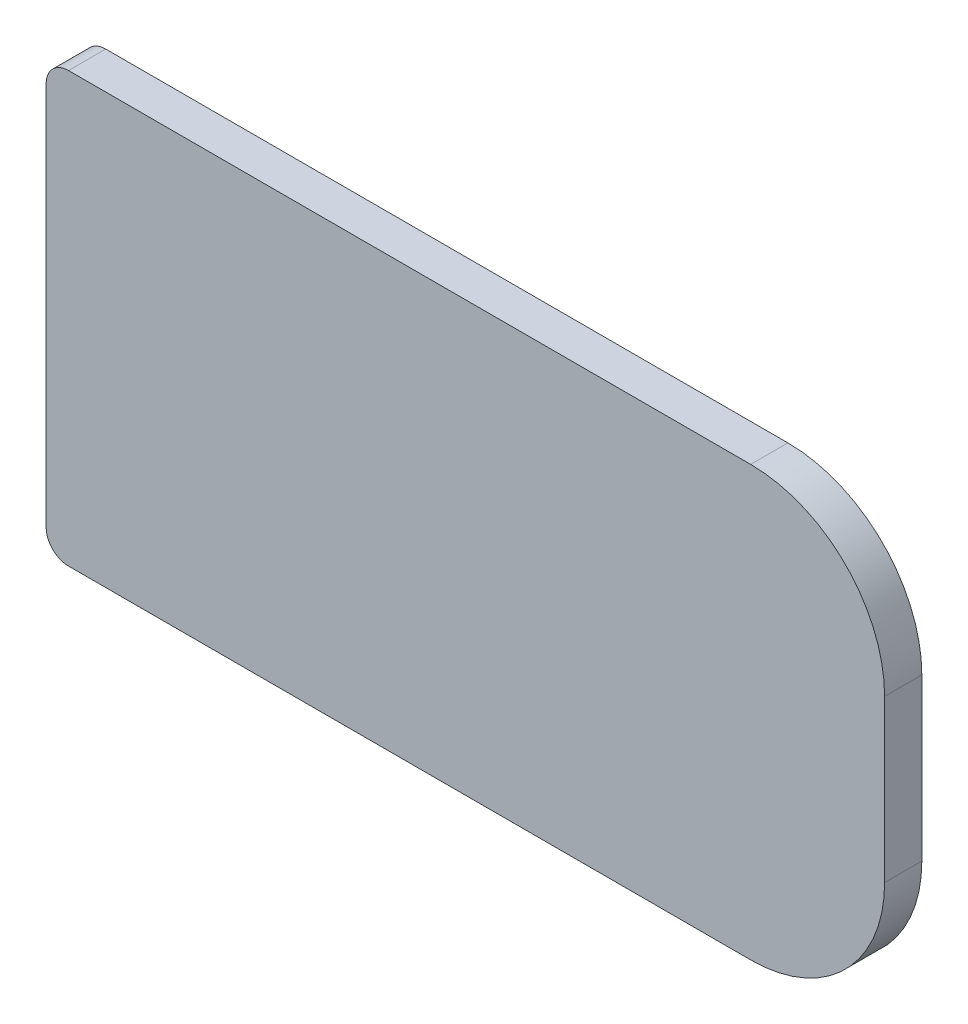
SolidWorks part; units mm, degrees
material "Pine"
ref_plane "Front Plane" through (0, 0, 0) normal (0, 0, 1) x (1, 0, 0)
ref_plane "Top Plane" through (0, 0, 0) normal (0, 1, 0) x (1, 0, 0)
ref_plane "Right Plane" through (0, 0, 0) normal (1, 0, 0) x (0, 0, -1)
sketch "Sketch1" plane through (0, 0, 0) normal (0, 0, 1) x (1, 0, 0)
  line L0 (23, 17.3) -> (-32, 17.3) construction
  line L1 (33.8, -6.5) -> (33.8, 6.5) construction
  line L2 (-32, -17.3) -> (23, -17.3) construction
  line L3 (-33.8, 15.5) -> (-33.8, -15.5) construction
  line L4 (23, 17.3) -> (-32, 17.3)
  line L5 (33.8, -6.5) -> (33.8, 6.5)
  line L6 (-32, -17.3) -> (23, -17.3)
  line L7 (-33.8, 15.5) -> (-33.8, -15.5)
  arc A0 (-32, 17.3) -> (-33.8, 15.5) centre (-32, 15.5) ccw construction
  arc A1 (33.8, 6.5) -> (23, 17.3) centre (23, 6.5) ccw construction
  arc A2 (23, -17.3) -> (33.8, -6.5) centre (23, -6.5) ccw construction
  arc A3 (-33.8, -15.5) -> (-32, -17.3) centre (-32, -15.5) ccw construction
  arc A4 (-32, 17.3) -> (-33.8, 15.5) centre (-32, 15.5) ccw
  arc A5 (33.8, 6.5) -> (23, 17.3) centre (23, 6.5) ccw
  arc A6 (23, -17.3) -> (33.8, -6.5) centre (23, -6.5) ccw
  arc A7 (-33.8, -15.5) -> (-32, -17.3) centre (-32, -15.5) ccw
extrude "Boss-Extrude1" add sketch "Sketch1" along normal blind 3
